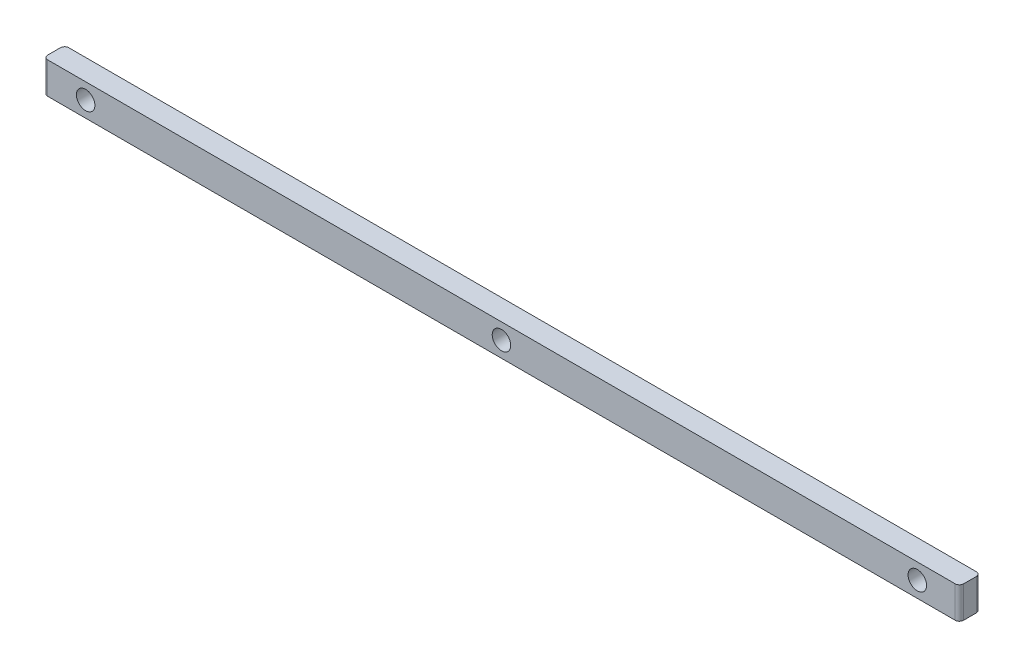
SolidWorks part; units mm, degrees
material "Balsa"
ref_plane "Front Plane" through (0, 0, 0) normal (0, 0, 1) x (1, 0, 0)
ref_plane "Top Plane" through (0, 0, 0) normal (0, 1, 0) x (1, 0, 0)
ref_plane "Right Plane" through (0, 0, 0) normal (1, 0, 0) x (0, 0, -1)
sketch "Sketch1" plane through (0, 0, 0) normal (0, 0, 1) x (1, 0, 0)
  line L1 (-276.225, -9.525) -> (276.225, -9.525)
  line L2 (-276.225, -9.525) -> (-276.225, 9.525)
  line L3 (-276.225, 9.525) -> (276.225, 9.525)
  line L4 (276.225, -9.525) -> (276.225, 9.525)
  line L5 (-276.225, -9.525) -> (276.225, 9.525) construction
  line L6 (-276.225, 9.525) -> (276.225, -9.525) construction
  point P0 (0, 0)
  dimension "D1" = 552.45
  dimension "D2" = 19.05
extrude "Boss-Extrude1" add sketch "Sketch1" along normal mid plane 12.7
sketch "Sketch2" plane through (0, 0, 6.35) normal (0, 0, 1) x (1, 0, 0)
  line L4 (276.225, -9.525) -> (276.225, 9.525)
  line L5 (276.225, 9.525) -> (-276.225, 9.525)
  line L6 (-276.225, 9.525) -> (-276.225, -9.525)
  line L7 (-276.225, -9.525) -> (276.225, -9.525)
  line L8 (276.225, -9.525) -> (276.225, 9.525)
  line L9 (276.225, 9.525) -> (-276.225, 9.525)
  line L10 (-276.225, 9.525) -> (-276.225, -9.525)
  line L11 (-276.225, -9.525) -> (276.225, -9.525)
  circle A0 centre (0, 0) radius 5.588
  circle A1 centre (250.825, 0) radius 5.588
  circle A2 centre (-250.825, 0) radius 5.588
  point P11 (0, 0)
  point P12 (0, 0)
  point P13 (0, 0)
  dimension "D2" = 11.176
  dimension "D3" = 250.825
  dimension "D4" = 250.825
  dimension "D5" = 9.525
  dimension "D6" = 9.525
  dimension "D1" = 0
extrude "Cut-Extrude1" cut sketch "Sketch2" against normal through all both and the other way through all contours A2 | A0 | A1
fillet "Fillet1" radius 2.54 4 edges at (-276.225, 0, -6.35) (-276.225, 0, 6.35) (276.225, 0, -6.35) (276.225, 0, 6.35)
